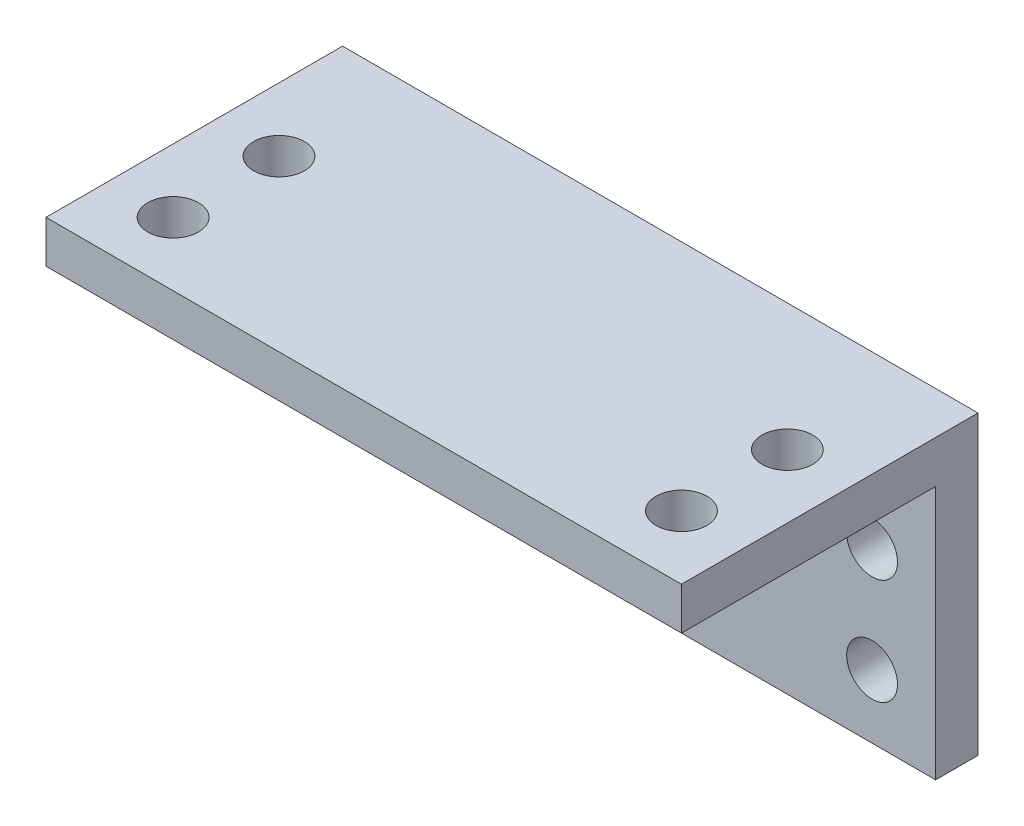
SolidWorks part; units mm, degrees
ref_plane "Front Plane" through (0, 0, 0) normal (0, 0, 1) x (1, 0, 0)
ref_plane "Top Plane" through (0, 0, 0) normal (0, 1, 0) x (1, 0, 0)
ref_plane "Right Plane" through (0, 0, 0) normal (1, 0, 0) x (0, 0, -1)
sketch "Sketch1" plane through (0, 0, 0) normal (1, 0, 0) x (0, 0, -1)
  line L0 (-2.1809, -19.4357) -> (15.5991, -19.4357)
  line L1 (15.5991, -19.4357) -> (15.5991, -37.2157)
  line L2 (15.5991, -37.2157) -> (13.0591, -37.2157)
  line L3 (13.0591, -37.2157) -> (13.0591, -21.9757)
  line L4 (13.0591, -21.9757) -> (-2.1809, -21.9757)
  line L5 (-2.1809, -21.9757) -> (-2.1809, -19.4357)
  dimension "D1" = 15.24
  dimension "D2" = 2.54
  dimension "D3" = 2.54
  dimension "D4" = 15.24
extrude "Boss-Extrude1" add sketch "Sketch1" along normal blind 38.1
sketch "Sketch2" plane through (0, 0, -15.5991) normal (0, 0, -1) x (-1, 0, 0)
  line L0 (-38.1, -37.2157) -> (-38.1, -19.4357) construction
  line L1 (-38.1, -37.2157) -> (0, -37.2157) construction
  circle A0 centre (-34.29, -33.4057) radius 1.524
  circle A1 centre (-3.81, -33.4057) radius 1.524
  circle A2 centre (-3.81, -27.0557) radius 1.524
  circle A3 centre (-34.29, -27.0557) radius 1.524
  dimension "D1" = 3.048
  dimension "D2" = 3.048
  dimension "D3" = 30.48
  dimension "D4" = 3.81
  dimension "D5" = 3.81
  dimension "D7" = 6.35
  dimension "D6" = 2
extrude "Cut-Extrude1" cut sketch "Sketch2" against normal through all
sketch "Sketch3" plane through (0, -19.4357, 0) normal (0, 1, 0) x (1, 0, 0)
  line L0 (0, 15.5991) -> (0, -2.1809) construction
  line L1 (38.1, -2.1809) -> (0, -2.1809) construction
  circle A0 centre (3.81, 1.6291) radius 1.524
  circle A1 centre (34.29, 1.6291) radius 1.524
  circle A2 centre (3.81, 7.9791) radius 1.524
  circle A3 centre (34.29, 7.9791) radius 1.524
  point P8 (3.81, 8.8646)
  dimension "D1" = 3.048
  dimension "D2" = 3.048
  dimension "D7" = 6.35
  dimension "D3" = 30.48
  dimension "D4" = 3.81
  dimension "D5" = 3.81
  dimension "D6" = 2
extrude "Cut-Extrude2" cut sketch "Sketch3" against normal through all
